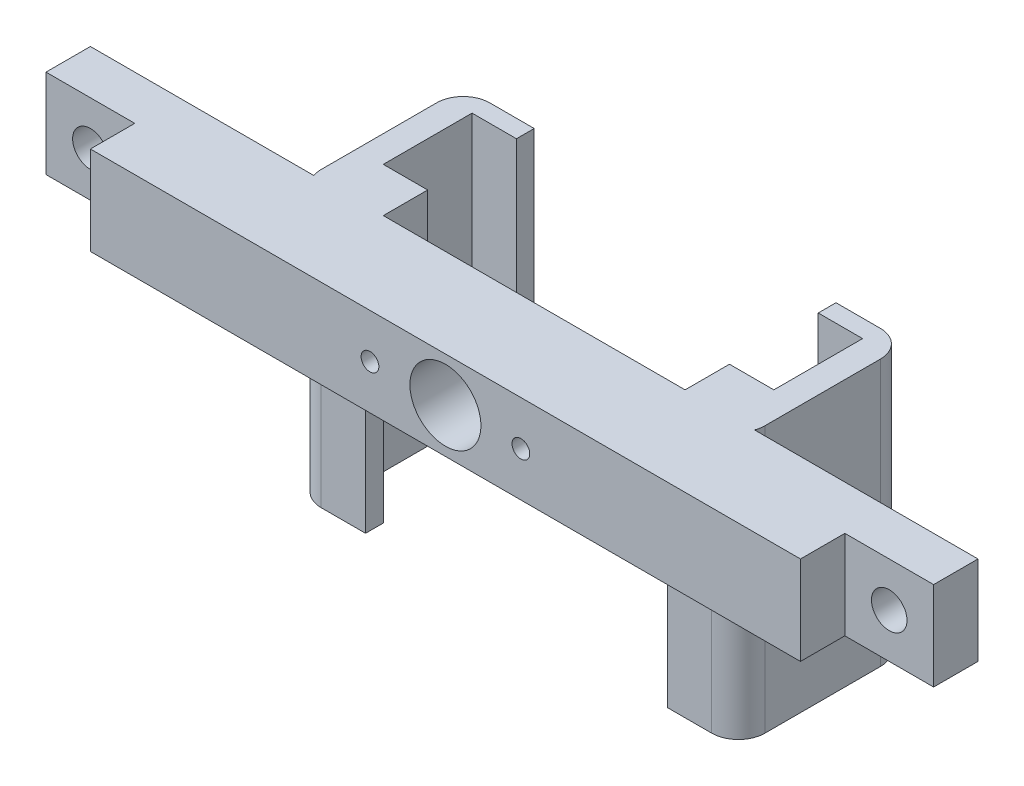
SolidWorks part; units mm, degrees
ref_plane "Front Plane" through (0, 0, 0) normal (0, 0, 1) x (1, 0, 0)
ref_plane "Top Plane" through (0, 0, 0) normal (0, 1, 0) x (1, 0, 0)
ref_plane "Right Plane" through (0, 0, 0) normal (1, 0, 0) x (0, 0, -1)
sketch "Sketch1" plane through (0, 0, 0) normal (0, 0, 1) x (1, 0, 0)
  line L1 (-50, 5) -> (50, 5)
  line L2 (-50, 5) -> (-50, -5)
  line L3 (-50, -5) -> (50, -5)
  line L4 (50, 5) -> (50, -5)
  line L5 (-50, 5) -> (50, -5) construction
  line L6 (-50, -5) -> (50, 5) construction
  point P0 (0, 0)
  dimension "D1" = 100
  dimension "D2" = 10
extrude "Boss-Extrude1" add sketch "Sketch1" along normal blind 10
sketch "Sketch2" plane through (0, 5, 0) normal (0, 1, 0) x (1, 0, 0)
  line L5 (-50, -10) -> (-40, -10)
  line L6 (-50, -10) -> (-50, -5)
  line L7 (-50, -5) -> (-40, -5)
  line L8 (-40, -10) -> (-40, -5)
  dimension "D1" = 10
  dimension "D2" = 5
sketch "Sketch6" plane through (0, 0, 0) normal (0, 0, -1) x (-1, 0, 0)
  line L0 (0, 5) -> (0, -5) construction
  line L1 (-25, 5) -> (-25, -5)
  line L3 (-25, 5) -> (-22, 5)
  line L4 (-50, 5) -> (-50, -5)
  line L5 (-50, -5) -> (50, -5)
  line L6 (-50, 5) -> (-50, -5)
  line L7 (50, 5) -> (-50, 5)
  line L9 (-50, -5) -> (50, -5)
  line L11 (50, 5) -> (-50, 5)
  line L12 (-22, 5) -> (-22, -5)
  line L13 (-22, -5) -> (-25, -5)
  line L17 (50, -5) -> (50, 5)
  line L18 (50, -5) -> (50, 5)
  line M11 (-50, -5) -> (50, -5)
  line M13 (50, 5) -> (-50, 5)
  dimension "D2" = 25
  dimension "D3" = 3
  dimension "D1" = 0
extrude "Boss-Extrude2" add sketch "Sketch6" along normal blind 17 contours L12 L1 M13 M11
sketch "Sketch8" plane through (22, 0, 0) normal (-1, 0, 0) x (0, 0, 1)
  line L0 (-17, -5) -> (0, -5) construction
  line L1 (-17, 5) -> (-15, 5)
  line L2 (-17, 5) -> (-17, -5)
  line L3 (-17, -5) -> (-15, -5)
  line L4 (-15, 5) -> (-15, -5)
  dimension "D1" = 2
extrude "Boss-Extrude3" add sketch "Sketch8" along normal blind 5
sketch "Sketch9" plane through (0, -5, 0) normal (0, -1, 0) x (1, 0, 0)
  line L0 (17, -17) -> (17, 0) construction
  line L1 (-50, 0) -> (22, 0) construction
  line L2 (17, 0) -> (22, 0)
  line L4 (17, 0) -> (17, 2)
  line L5 (17, 2) -> (25, 2)
  line L6 (25, 0) -> (25, 2)
  line L7 (22, 0) -> (22, -15)
  line L8 (22, -15) -> (17, -15)
  line L9 (17, -15) -> (17, -17)
  line L10 (17, -17) -> (25, -17)
  line L11 (25, -17) -> (25, 0)
  line L12 (25, 0) -> (25, 2)
  line L13 (-50, 10) -> (-50, 0) construction
  line L14 (-50, 10) -> (50, 10) construction
  line M16 (-50, 0) -> (22, 0)
  line M17 (22, 0) -> (22, -15)
  line M18 (22, -15) -> (17, -15)
  line M19 (17, -15) -> (17, -17)
  line M20 (17, -17) -> (25, -17)
  line M21 (25, -17) -> (25, 0)
  dimension "D1" = 8
  dimension "D2" = 2
  dimension "D3" = 2
extrude "Boss-Extrude4" add sketch "Sketch9" along normal blind 20 contours L6 L5 L4 M21 M16 M17 M18 M19 M20
mirror "Mirror3" about plane through (0, 0, 0) normal (1, 0, 0) of "Boss-Extrude4", "Boss-Extrude3", "Boss-Extrude2"
extrude "Cut-Extrude1" cut sketch "Sketch2" against normal blind 10
mirror "Mirror4" about plane through (0, 0, 0) normal (1, 0, 0) of "Cut-Extrude1"
sketch "Sketch10" plane through (0, 0, 5) normal (0, 0, 1) x (1, 0, 0)
  line L0 (50, -5) -> (50, 5) construction
  line L1 (40, -5) -> (50, -5) construction
  circle A0 centre (45, 0) radius 2
  dimension "D1" = 4
  dimension "D2" = 5
  dimension "D3" = 5
extrude "Cut-Extrude2" cut sketch "Sketch10" against normal up to next
mirror "Mirror5" about plane through (0, 0, 0) normal (1, 0, 0) of "Cut-Extrude2"
sketch "Sketch12" plane through (0, 0, 0) normal (0, 0, -1) x (-1, 0, 0)
  line L0 (0, 5) -> (0, -5) construction
  line L1 (-22, 5) -> (22, 5) construction
  line L2 (17, -5) -> (-17, -5) construction
sketch "Sketch13" plane through (0, 0, 0) normal (0, 0, -1) x (-1, 0, 0)
  line L0 (0, 0) -> (-8.5, 0) construction
  line L1 (0, 0) -> (8.5, 0) construction
  circle A0 centre (0, 0) radius 4
  circle A1 centre (-8.5, 0) radius 1
  circle A2 centre (8.5, 0) radius 1
  dimension "D1" = 8
  dimension "D4" = 2
  dimension "D5" = 2
  dimension "D2" = 8.5
  dimension "D3" = 8.5
extrude "Cut-Extrude3" cut sketch "Sketch13" against normal through all
fillet "Fillet1" radius 3 2 edges at (25, -10, -17) (-25, -10, -17)
fillet "Fillet2" radius 3 2 edges at (-25, -15, 2) (25, -15, 2)
sketch "Sketch14" plane through (0, 0, 0) normal (0, 0, -1) x (-1, 0, 0)
  line L0 (17, -5) -> (-17, -5) construction
  line L1 (22, 5) -> (17, 5)
  line L2 (22, 5) -> (22, -5)
  line L3 (22, -5) -> (17, -5)
  line L4 (17, 5) -> (17, -5)
  dimension "D1" = 5
extrude "Boss-Extrude5" add sketch "Sketch14" along normal blind 5
mirror "Mirror6" about plane through (0, 0, 0) normal (1, 0, 0) of "Boss-Extrude5"
